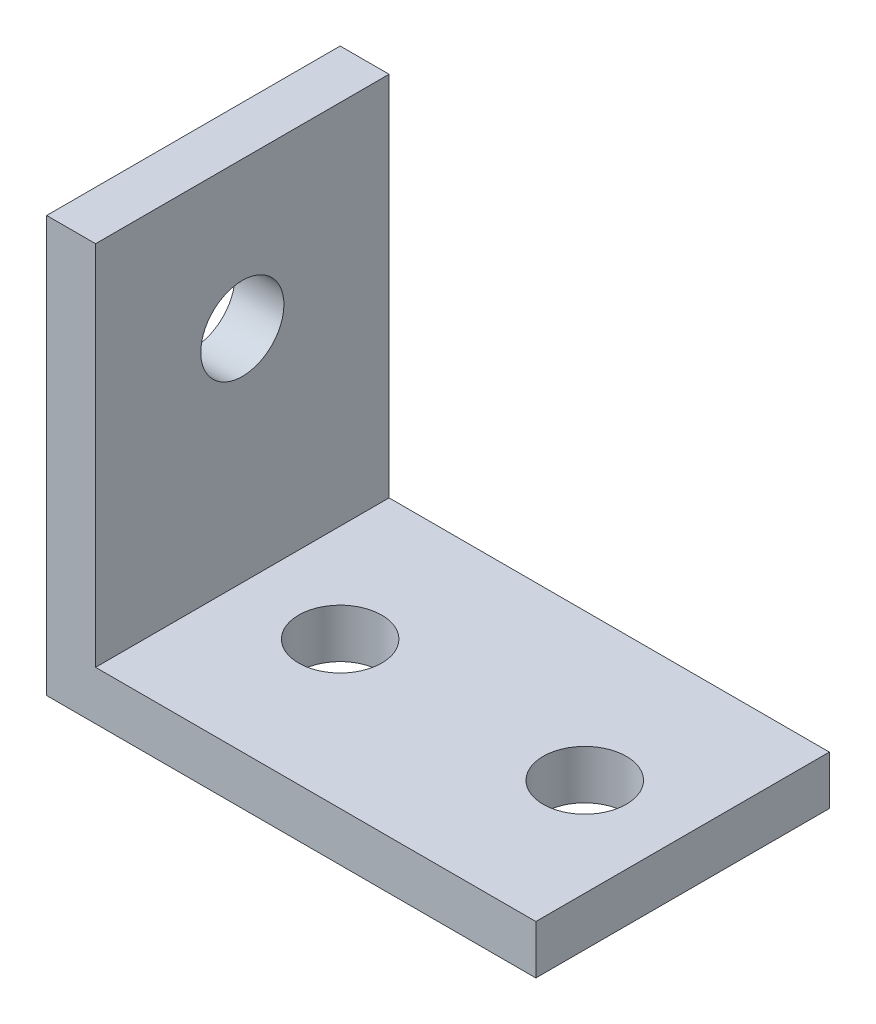
SolidWorks part; units mm, degrees
ref_plane "Front Plane" through (0, 0, 0) normal (0, 0, 1) x (1, 0, 0)
ref_plane "Top Plane" through (0, 0, 0) normal (0, 1, 0) x (1, 0, 0)
ref_plane "Right Plane" through (0, 0, 0) normal (1, 0, 0) x (0, 0, -1)
sketch "Sketch3" plane through (0, 0, 0) normal (0, 0, 1) x (1, 0, 0)
  line L0 (0, 0) -> (10, 0)
  line L1 (10, 0) -> (10, 1)
  line L2 (10, 1) -> (1, 1)
  line L3 (1, 1) -> (1, 8.5)
  line L4 (1, 8.5) -> (0, 8.5)
  line L5 (0, 8.5) -> (0, 0)
  dimension "D1" = 10
  dimension "D2" = 8.5
  dimension "D3" = 1
  dimension "D4" = 1
extrude "Boss-Extrude2" add sketch "Sketch3" along normal blind 6
sketch "Sketch4" plane through (1, 0, 0) normal (1, 0, 0) x (0, 0, -1)
  line L0 (-6, 8.5) -> (0, 8.5) construction
  line L1 (-6, 8.5) -> (0, 8.5) construction
  circle A0 centre (-3, 5.5) radius 0.85
  point P8 (-3, 8.5)
  dimension "D1" = 3
  dimension "D2" = 1.7
extrude "Cut-Extrude1" cut sketch "Sketch4" against normal blind 6
sketch "Sketch6" plane through (0, 1, 0) normal (0, 1, 0) x (1, 0, 0)
  line L0 (3, -3) -> (8, -3) construction
  line L1 (1, -6) -> (10, -6) construction
  line L2 (10, -6) -> (10, 0) construction
  line L3 (10, -6) -> (10, 0) construction
  circle A0 centre (3, -3) radius 0.85
  circle A1 centre (8, -3) radius 0.85
  point P8 (5.5, -3)
  point P9 (5.5, -6)
  point P12 (3, -2.0402)
  point P15 (10, -3)
  dimension "D1" = 2
  dimension "D2" = 1.7
  dimension "D3" = 1.7
extrude "Cut-Extrude2" cut sketch "Sketch6" against normal blind 6
